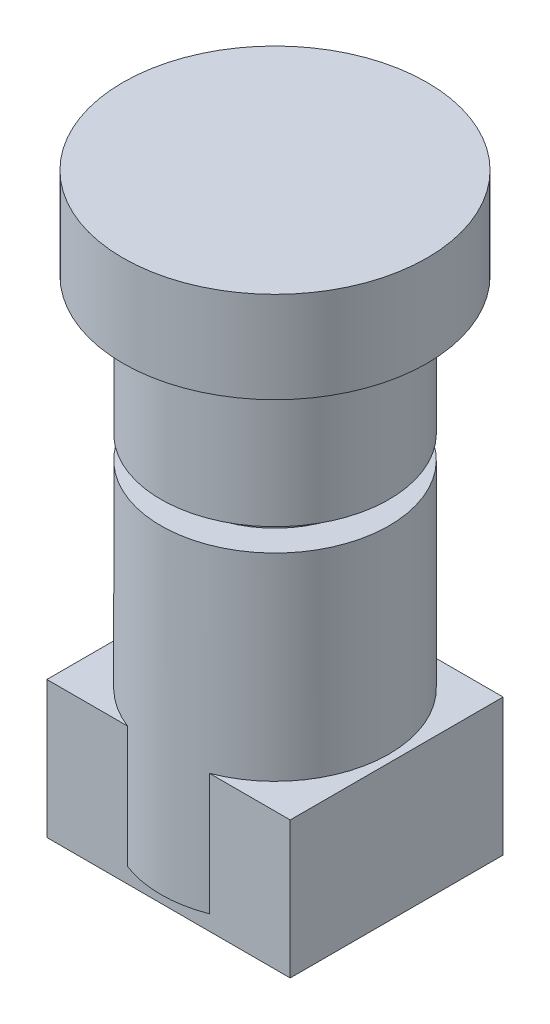
SolidWorks part; units mm, degrees
ref_plane "Front Plane" through (0, 0, 0) normal (0, 0, 1) x (1, 0, 0)
ref_plane "Top Plane" through (0, 0, 0) normal (0, 1, 0) x (1, 0, 0)
ref_plane "Right Plane" through (0, 0, 0) normal (1, 0, 0) x (0, 0, -1)
sketch "SK_P01_Mushroomandbody" plane through (0, 0, 0) normal (0, 0, 1) x (1, 0, 0)
  line L0 (0, 2) -> (15, 2)
  line L1 (15, 2) -> (15, 44)
  line L2 (15, 44) -> (11, 44)
  line L3 (11, 44) -> (11, 47)
  line L4 (11, 47) -> (15, 47)
  line L5 (15, 47) -> (15, 65)
  line L6 (15, 65) -> (20, 65)
  line L7 (20, 65) -> (20, 77)
  line L8 (20, 77) -> (0, 77)
  line L9 (0, 77) -> (0, 2)
  line L10 (0, -3) -> (0, 82) construction
revolve "P01_Mushroomandbody" add sketch "SK_P01_Mushroomandbody" angle 360 about L10
sketch "SK_P02_ContactblocksNC1NC2" plane through (0, 0, 0) normal (0, 1, 0) x (1, 0, 0)
  line L0 (-16, -14) -> (16, -14)
  line L1 (16, -14) -> (16, 14)
  line L2 (16, 14) -> (-16, 14)
  line L3 (-16, 14) -> (-16, -14)
extrude "P02_ContactblocksNC1NC2" add sketch "SK_P02_ContactblocksNC1NC2" along normal blind 18
